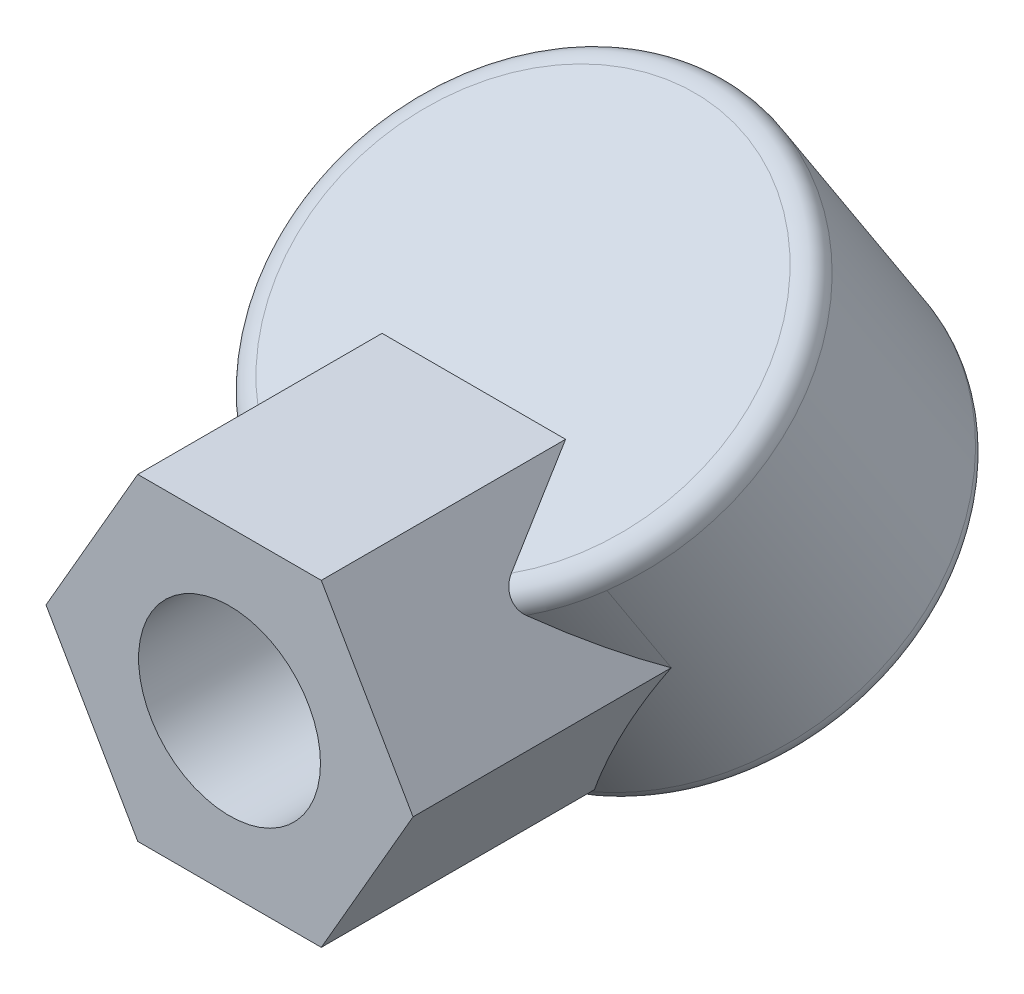
SolidWorks part; units mm, degrees
ref_plane "Płaszczyzna przednia" through (0, 0, 0) normal (0, 0, 1) x (1, 0, 0)
ref_plane "Płaszczyzna górna" through (0, 0, 0) normal (0, 1, 0) x (1, 0, 0)
ref_plane "Płaszczyzna prawa" through (0, 0, 0) normal (1, 0, 0) x (0, 0, -1)
sketch "Szkic3" plane through (0, 0, 0) normal (1, 0, 0) x (0, 0, -1)
  line L2 (0, 0) -> (-36.5355, 0) construction
  line L3 (0, 0) -> (-14.1606, 21.8054) construction
  line L4 (0, 0) -> (-28.2259, -18.3301) construction
  line L5 (-7.0803, 10.9027) -> (-15.467, 5.4563)
  line L6 (-15.467, 5.4563) -> (-8.3867, -5.4464)
  line L8 (-3.8125, 5.8707) -> (-7.0803, 10.9027)
  line L9 (-8.3867, -5.4464) -> (-1.3867, -6.8613)
  arc A2 (-3.8125, 5.8707) -> (-1.3867, -6.8613) centre (0, 0) ccw
  dimension "D1" = 14
  dimension "D2" = 33
  dimension "D3" = 10
  dimension "D4" = 13
  dimension "D5" = 7
revolve "Obrót1" add sketch "Szkic3" angle 360 about L8
sketch "Szkic4" plane through (0, 0, 0) normal (0, 0, 1) x (1, 0, 0)
  line L1 (-8.1132, 4.4169) -> (-7.8818, -4.8178)
  line L2 (-7.8818, -4.8178) -> (0.2314, -9.2347)
  line L3 (0.2314, -9.2347) -> (8.1132, -4.4169)
  line L4 (8.1132, -4.4169) -> (7.8818, 4.8178)
  line L5 (7.8818, 4.8178) -> (-0.2314, 9.2347)
  line L6 (-0.2314, 9.2347) -> (-8.1132, 4.4169)
  circle A0 centre (0, 0) radius 8 construction
  dimension "D1" = 16
ref_plane "Płaszczyzna1" through (0, 0, 20) normal (0, 0, 1) x (1, 0, 0)
sketch "Szkic5" plane through (0, 0, 20) normal (0, 0, 1) x (1, 0, 0)
  line L1 (8.0829, 2.5) -> (4.0473, 9.4899)
  line L2 (4.0473, 9.4899) -> (-4.024, 9.4899)
  line L3 (-4.024, 9.4899) -> (-8.0597, 2.5)
  line L4 (-8.0597, 2.5) -> (-4.024, -4.4899)
  line L5 (-4.024, -4.4899) -> (4.0473, -4.4899)
  line L6 (4.0473, -4.4899) -> (8.0829, 2.5)
  line L7 (0.0116, 2.5) -> (16.5506, 2.5) construction
  circle A0 centre (0.0116, 2.5) radius 6.9899 construction
  circle A1 centre (0.0116, 2.5) radius 4
  point P10 (0, 0)
  dimension "D1" = 8
  dimension "D2" = 13.9799
  dimension "D3" = 2.5
extrude "Dodanie-wyciągnięcie2" add sketch "Szkic5" against normal up to next
fillet "Zaokrąglenie1" radius 1 2 edges at (0, 5.4464, -8.3867) (-0.0116, 16.3491, -1.3064)
